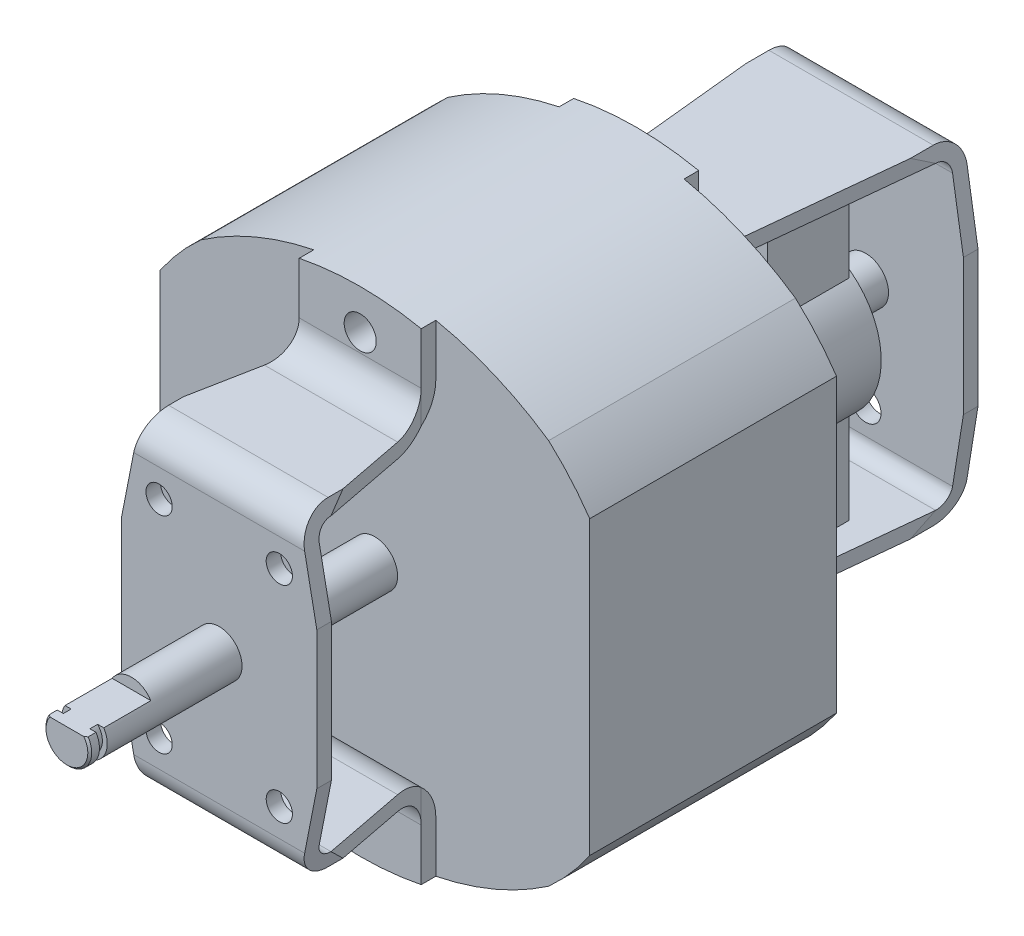
SolidWorks part; units mm, degrees
material "PW50:12:C1:0:1:2:Re:26:"
ref_plane "Plane1" through (0, 0, 0) normal (0, 0, 1) x (1, 0, 0)
ref_plane "Plane2" through (0, 0, 0) normal (0, 1, 0) x (1, 0, 0)
ref_plane "Plane3" through (0, 0, 0) normal (1, 0, 0) x (0, 0, -1)
sketch "motor core shape" plane through (0, 0, 0) normal (0, 0, 1) x (1, 0, 0)
  line L0 (-5.8998, 26.05) -> (5.8998, 26.05)
  line L1 (-22.1, 15) -> (-22.1, -15)
  line L2 (5.8998, -26.05) -> (-5.8998, -26.05)
  line L3 (22.1, -15) -> (22.1, 15)
  arc A0 (-5.8998, 26.05) -> (-22.1, 15) centre (0, 0) ccw
  arc A1 (-22.1, -15) -> (-5.8998, -26.05) centre (0, 0) ccw
  arc A2 (5.8998, -26.05) -> (22.1, -15) centre (0, 0) ccw
  arc A3 (22.1, 15) -> (5.8998, 26.05) centre (0, 0) ccw
  dimension "D1" = 44.2
  dimension "D2" = 52.1
  dimension "D3" = 30
  dimension "D4" = 11.7996
extrude "motor core" add sketch "motor core shape" along normal blind 25.38
sketch "Sketch5" plane through (0, 0, 25.38) normal (0, 0, 1) x (1, 0, 0)
  line L0 (0, 30.7658) -> (0, -31.4186) construction
  line L1 (-27.6647, 0) -> (27.0118, 0) construction
  line L2 (-5.8998, 26.05) -> (5.8998, 26.05) construction
  line L5 (8.2, 16.45) -> (10.04, 7.075)
  line L6 (-8.2, 16.45) -> (-10.04, 7.075)
  line L7 (10.04, 7.075) -> (10.04, -7.075)
  line L8 (-10.04, 7.075) -> (-10.04, -7.075)
  line L9 (-8.2, -16.45) -> (-10.04, -7.075)
  line L10 (8.2, -16.45) -> (10.04, -7.075)
  line L15 (-8.2, 16.45) -> (8.2, 16.45)
  line L16 (-8.2, -16.45) -> (8.2, -16.45)
  point P9 (0, 25.95)
  point P16 (-10.04, 0)
  point P17 (10.04, 0)
  point P21 (0, -25.95)
  dimension "D1" = 16.4
  dimension "D2" = 9.6
  dimension "D4" = 20.08
  dimension "D5" = 14.15
extrude "gear end plate" add sketch "Sketch5" along normal blind 16
fillet "gear end plate fillet" radius 3 2 edges at (0, -16.45, 41.38) (-8.2, 16.45, 33.38)
sketch "Sketch7" plane through (-10.04, 0, 0) normal (-1, 0, 0) x (0, 0, 1)
  line L0 (25.38, 15) -> (25.38, -15) construction
  line L1 (25.38, 14.95) -> (25.38, -14.95)
  line L5 (38.38, -14.95) -> (25.38, -14.95)
  line L6 (39.88, -13.45) -> (39.88, -7.075)
  line L7 (39.88, 7.075) -> (39.88, -7.075)
  line L8 (39.88, 13.45) -> (39.88, 7.075)
  line L9 (38.38, 14.95) -> (25.38, 14.95)
  line L10 (38.38, -14.95) -> (25.38, -14.95)
  line L11 (39.88, -13.45) -> (39.88, -7.075)
  line L12 (39.88, 7.075) -> (39.88, -7.075)
  line L13 (39.88, 13.45) -> (39.88, 7.075)
  line L14 (38.38, 14.95) -> (25.38, 14.95)
  arc A2 (38.38, -14.95) -> (39.88, -13.45) centre (38.38, -13.45) ccw
  arc A3 (39.88, 13.45) -> (38.38, 14.95) centre (38.38, 13.45) ccw
  arc A4 (38.38, -14.95) -> (39.88, -13.45) centre (38.38, -13.45) ccw
  arc A5 (39.88, 13.45) -> (38.38, 14.95) centre (38.38, 13.45) ccw
  dimension "D1" = 1.5
extrude "gear end plate cut" cut sketch "Sketch7" against normal through all
sketch "Sketch8" plane through (0, 0, 25.38) normal (0, 0, 1) x (1, 0, 0)
  line L0 (0, 16.45) -> (0, -16.45) construction
  line L1 (6.275, 25.95) -> (6.275, 16.45)
  line L2 (-30.1129, 0) -> (30.1129, 0) construction
  line L3 (-6.275, -25.95) -> (-6.275, -16.45)
  line L4 (5.8998, -25.95) -> (-5.8998, -25.95)
  line L5 (6.275, -25.95) -> (-6.275, -25.95)
  line L6 (-6.275, 25.95) -> (-6.275, 16.45)
  line L7 (6.275, -25.95) -> (6.275, -16.45)
  line L8 (8.2, -16.45) -> (-8.2, -16.45) construction
  line L9 (6.275, 16.45) -> (-6.275, 16.45)
  line L10 (6.275, -16.45) -> (-6.275, -16.45)
  line L12 (6.275, 25.95) -> (-6.275, 25.95)
  point P19 (0, 0)
  dimension "D2" = 12.55
  dimension "D1" = 0.1
extrude "gear end plate tabs" add sketch "Sketch8" along normal blind 1.5
sketch "Sketch9" plane through (0, -16.45, 0) normal (0, -1, 0) x (1, 0, 0)
  line L0 (-8.2, 25.38) -> (-6.275, 25.38) construction
  line L1 (6.275, 25.38) -> (8.2, 25.38) construction
  line L2 (-8.4944, 25.38) -> (-6.275, 25.38)
  line L3 (6.275, 25.38) -> (8.4944, 25.38)
  line L6 (-8.4944, 38.38) -> (-8.4944, 25.38) construction
  line L7 (8.4944, 38.38) -> (6.275, 26.88)
  line L8 (-6.275, 26.88) -> (-6.275, 25.38) construction
  line L9 (6.275, 26.88) -> (6.275, 25.38) construction
  line L10 (-6.275, 26.88) -> (-6.275, 25.38)
  line L11 (6.275, 26.88) -> (6.275, 25.38)
  line L12 (-6.275, 26.88) -> (-8.4944, 38.38)
  line L13 (-8.4944, 38.38) -> (-8.4944, 25.38)
  line L14 (8.4944, 38.38) -> (8.4944, 25.38) construction
  line L15 (8.4944, 38.38) -> (8.4944, 25.38)
extrude "gear end side cut" cut sketch "Sketch9" against normal through all
fillet "gear end tab fillet" radius 3 2 edges at (0, -16.45, 26.88) (0, 16.45, 26.88)
sketch "Sketch10" plane through (-6.275, 0, 0) normal (-1, 0, 0) x (0, 0, 1)
  line L0 (25.38, 19.45) -> (25.38, 14.95)
  line L2 (29.88, 14.95) -> (25.38, 14.95)
  line L3 (29.88, -14.95) -> (25.38, -14.95)
  line L4 (25.38, -19.45) -> (25.38, -14.95)
  arc A3 (25.38, 19.45) -> (29.88, 14.95) centre (29.88, 19.45) ccw
  arc A4 (25.38, 19.45) -> (29.88, 14.95) centre (29.88, 19.45) ccw
  arc A5 (29.88, -14.95) -> (25.38, -19.45) centre (29.88, -19.45) ccw
  arc A6 (29.88, -14.95) -> (25.38, -19.45) centre (29.88, -19.45) ccw
  dimension "D1" = 1.5
  dimension "D2" = 1.5
extrude "gear end kludge fillet" cut sketch "Sketch10" against normal through all and the other way through all
sketch "Sketch11" plane through (0, 0, 41.38) normal (0, 0, 1) x (1, 0, 0)
  line L0 (0, -20.7281) -> (0, 30.0313) construction
  line L1 (-15.0973, 0) -> (30.1129, 0) construction
  circle A0 centre (6.1825, 10.5986) radius 1.35
  circle A1 centre (-6.1825, 10.5986) radius 1.35
  circle A2 centre (-6.1825, -10.5986) radius 1.35
  circle A3 centre (6.1825, -10.5986) radius 1.35
  dimension "D1" = 27.24
  dimension "D2" = 2.7
extrude "gear caddy screw holes" cut sketch "Sketch11" against normal up to next
sketch "Sketch13" plane through (0, 0, 0) normal (0, 0, -1) x (-1, 0, 0)
  line L0 (0, 16.95) -> (0, -16.95) construction
  line L1 (-10.05, 0) -> (10.05, 0) construction
  line L2 (-8.45, 16.95) -> (8.45, 16.95)
  line L3 (8.45, 16.95) -> (10.05, 7)
  line L4 (-10.05, 7) -> (-10.05, -7)
  line L5 (10.05, 7) -> (10.05, -7)
  line L6 (-8.45, 16.95) -> (-10.05, 7)
  line L7 (-8.45, -16.95) -> (-10.05, -7)
  line L8 (8.45, -16.95) -> (10.05, -7)
  line L9 (-8.45, -16.95) -> (8.45, -16.95)
  point P5 (-10.05, 0)
  point P10 (0, 16.45)
  point P12 (0, 16.95)
  point P15 (-10.04, 0)
  point P16 (10.04, 0)
  point P17 (10.05, 0)
  point P18 (0, -16.45)
  point P19 (0, -16.95)
  dimension "D1" = 14
  dimension "D2" = 33.9
  dimension "D3" = 16.9
  dimension "D4" = 20.1
extrude "rotor end plate" add sketch "Sketch13" along normal blind 26.6
fillet "rotor end plate fillet" radius 3 2 edges at (0, 16.95, -26.6) (8.45, -16.95, -13.3)
sketch "Sketch14" plane through (10.05, 0, 0) normal (1, 0, 0) x (0, 0, -1)
  line L0 (0, -15) -> (0, 15) construction
  line L1 (0, -15.45) -> (0, 15.45)
  line L5 (23.6, -15.45) -> (0, -15.45)
  line L6 (25.1, -13.95) -> (25.1, -7)
  line L7 (25.1, 7) -> (25.1, -7)
  line L8 (25.1, 13.95) -> (25.1, 7)
  line L9 (23.6, 15.45) -> (0, 15.45)
  line L10 (23.6, -15.45) -> (0, -15.45)
  line L11 (25.1, -13.95) -> (25.1, -7)
  line L12 (25.1, 7) -> (25.1, -7)
  line L13 (25.1, 13.95) -> (25.1, 7)
  line L14 (23.6, 15.45) -> (0, 15.45)
  arc A2 (23.6, -15.45) -> (25.1, -13.95) centre (23.6, -13.95) ccw
  arc A3 (25.1, 13.95) -> (23.6, 15.45) centre (23.6, 13.95) ccw
  arc A4 (23.6, -15.45) -> (25.1, -13.95) centre (23.6, -13.95) ccw
  arc A5 (25.1, 13.95) -> (23.6, 15.45) centre (23.6, 13.95) ccw
  dimension "D1" = 1.5
extrude "rotor end plate cut" cut sketch "Sketch14" against normal through all and the other way through all
sketch "Sketch15" plane through (0, 0, 0) normal (0, 0, -1) x (-1, 0, 0)
  line L0 (-6.425, 25.95) -> (6.425, 25.95)
  line L1 (-6.425, 25.95) -> (-6.425, 16.95)
  line L2 (-8.45, 16.95) -> (8.45, 16.95) construction
  line L3 (-6.425, 16.95) -> (6.425, 16.95)
  line L4 (0, 30.1945) -> (0, -31.9899) construction
  line L5 (-30.3577, 0) -> (31.9899, 0) construction
  line L6 (6.425, 25.95) -> (6.425, 16.95)
  line L7 (6.425, -25.95) -> (6.425, -16.95)
  line L8 (-6.425, -16.95) -> (6.425, -16.95)
  line L9 (-6.425, -25.95) -> (-6.425, -16.95)
  line L10 (-6.425, -25.95) -> (6.425, -25.95)
  line L11 (5.8998, 26.05) -> (-5.8998, 26.05) construction
  point P13 (0, 16.95)
  point P14 (0, 25.95)
  point P18 (0, -25.95)
  point P19 (0, -16.95)
  dimension "D1" = 12.85
  dimension "D2" = 0.1
extrude "rotor end plate tabs" add sketch "Sketch15" along normal blind 1.5
sketch "Sketch16" plane through (0, -16.95, 0) normal (0, -1, 0) x (1, 0, 0)
  line L2 (-8.6912, -23.6) -> (-8.6912, 0) construction
  line L3 (-6.425, -1.5) -> (-6.425, 0) construction
  line L4 (6.425, -1.5) -> (6.425, 0) construction
  line L5 (8.6912, -23.6) -> (8.6912, 0) construction
  line L6 (-8.6912, -23.6) -> (-8.6912, 0)
  line L7 (-6.425, -1.5) -> (-6.425, 0)
  line L8 (6.425, -1.5) -> (6.425, 0)
  line L9 (8.6912, -23.6) -> (8.6912, 0)
  line L10 (8.6912, 0) -> (6.425, 0)
  line L11 (6.425, -1.5) -> (8.6912, -23.6)
  line L12 (-6.425, 0) -> (-8.6912, 0)
  line L13 (-6.425, -1.5) -> (-8.6912, -23.6)
extrude "rotor end side ct" cut sketch "Sketch16" against normal through all and the other way through all
fillet "rotor end tab fillet" radius 3 2 edges at (0, -16.95, -1.5) (0, 16.95, -1.5)
sketch "Sketch17" plane through (-6.425, 0, 0) normal (-1, 0, 0) x (0, 0, 1)
  line L0 (0, 19.95) -> (0, 15.45)
  line L2 (-4.5, 15.45) -> (0, 15.45)
  line L3 (0, -19.95) -> (0, -15.45)
  line L5 (-4.5, -15.45) -> (0, -15.45)
  arc A1 (-4.5, 15.45) -> (0, 19.95) centre (-4.5, 19.95) ccw
  arc A2 (-4.5, 15.45) -> (0, 19.95) centre (-4.5, 19.95) ccw
  arc A3 (0, -19.95) -> (-4.5, -15.45) centre (-4.5, -19.95) ccw
  arc A4 (0, -19.95) -> (-4.5, -15.45) centre (-4.5, -19.95) ccw
  dimension "D1" = 1.5
  dimension "D2" = 1.5
extrude "rotor end kludge fillet" cut sketch "Sketch17" against normal through all and the other way through all
sketch "Sketch12" plane through (0, 0, 0) normal (0, 0, -1) x (-1, 0, 0)
  line L0 (-28.8072, 0) -> (27.0118, 0) construction
  line L1 (5.8998, 26.05) -> (-5.8998, 26.05) construction
  circle A0 centre (0, 21.3) radius 1.65
  circle A1 centre (0, -21.3) radius 1.65
  dimension "D1" = 3.3
  dimension "D2" = 4.75
extrude "motor long screw holes" cut sketch "Sketch12" against normal through all and the other way through all
sketch "Sketch1" plane through (0, 0, 25.38) normal (0, 0, 1) x (1, 0, 0)
  circle A0 centre (0, 0) radius 2.35
  dimension "D1" = 4.7
extrude "motor shaft" add sketch "Sketch1" along normal blind 31.66 and the other way offset from surface (54.08 mm away) 28.7 other way up to face at (0, -26.0004, 0)
sketch "Sketch3" plane through (0, 0, 57.04) normal (0, 0, 1) x (1, 0, 0)
  circle A0 centre (0, 0) radius 2.35 construction
  circle A1 centre (0, 0) radius 1.85
  circle A2 centre (0, 0) radius 1.85
  circle A3 centre (0, 0) radius 2.35
  dimension "D1" = 0.5
extrude "groove cut" cut sketch "Sketch3" against normal blind 1.8
sketch "Sketch4" plane through (0, 0, 57.04) normal (0, 0, 1) x (1, 0, 0)
  circle A0 centre (0, 0) radius 2.35 construction
  circle A1 centre (0, 0) radius 2.35
extrude "groove fill" add sketch "Sketch4" against normal offset from surface (1 mm away) 0.8 up to face at (1.85, 0, 55.24)
chamfer "shaft chamfer" distance 0.2 angle 45 1 edges at (2.35, 0, 57.04)
sketch "Sketch2" plane through (0, 0, 57.04) normal (0, 0, 1) x (1, 0, 0)
  line L0 (-1.99, 1.25) -> (1.99, 1.25)
  circle A0 centre (0, 0) radius 2.35 construction
  arc A1 (1.99, 1.25) -> (-1.99, 1.25) centre (0, 0) ccw
  dimension "D1" = 3.6
extrude "motor gear flat" cut sketch "Sketch2" against normal blind 6.64
sketch "Sketch18" plane through (0, 0, -26.6) normal (0, 0, -1) x (-1, 0, 0)
  line L0 (-33.3772, 0) -> (32.8875, 0) construction
  circle A0 centre (0, 11.12) radius 1.58
  circle A1 centre (0, -11.12) radius 1.58
  dimension "D1" = 3.16
  dimension "D2" = 25.4
extrude "rotor end plate holes" cut sketch "Sketch18" against normal up to next
ref_plane "Plane4" through (0, 0, -18.7) normal (0, 0, -1) x (-1, 0, 0)
sketch "Sketch20" plane through (0, 0, -18.7) normal (0, 0, -1) x (-1, 0, 0)
  circle A1 centre (0, 0) radius 2.35 construction
  circle A2 centre (0, 0) radius 2.35
  circle A3 centre (0, 0) radius 8
  dimension "D1" = 16
extrude "motor rotor" add sketch "Sketch20" against normal blind 12
sketch "Sketch21" plane through (0, 16.95, 0) normal (0, 1, 0) x (-1, 0, 0)
  line L0 (0, 0) -> (0, -32.7148) construction
  line L1 (0, 0) -> (0, -6.7) construction
  line L2 (5.1372, -18.2466) -> (-5.1372, -18.2466)
  line L3 (-5.1372, -18.2466) -> (-5.1372, -9.8593)
  line L4 (5.1372, -18.2466) -> (5.1372, -9.8593)
  line L5 (-5.1372, -9.8593) -> (5.1372, -9.8593)
  point P8 (0, -18.2466)
  point P11 (0, -9.8593)
extrude "motor stator,brushes" add sketch "Sketch21" along normal up to surface (33.9 mm away)
sketch "Sketch22" plane through (0, 0, 26.88) normal (0, 0, 1) x (1, 0, 0)
  line L0 (0, 0) -> (15.3278, 0) construction
  line L1 (28.8072, 0) -> (-27.0118, 0) construction
  line L3 (-5.8998, 26.05) -> (6.425, 25.9255)
  line L4 (-5.8998, -26.05) -> (6.425, -25.9255)
  arc A0 (31.4115, -2.6863) -> (-31.3668, -2.3101) centre (0, -6.2245) ccw construction
  arc A1 (17.8771, -19.8448) -> (6.425, -25.9255) centre (0, 0) cw
  arc A2 (-5.8998, -26.05) -> (-17.8771, -19.8448) centre (0, 0) cw
  arc A3 (17.8771, 19.8448) -> (-17.8771, 19.8448) centre (0, -6.2245) ccw
  arc A4 (-5.8998, 26.05) -> (-6.3251, 25.95) centre (0, 0) ccw construction
  arc A5 (-5.8998, 26.05) -> (-17.8771, 19.8448) centre (0, 0) ccw
  arc A6 (22.1, 15) -> (6.425, 25.9255) centre (0, 0) ccw construction
  arc A7 (17.8771, 19.8448) -> (6.425, 25.9255) centre (0, 0) ccw
  arc A8 (17.8771, -19.8448) -> (-17.8771, -19.8448) centre (0, 6.2245) cw
extrude "Cut-Extrude1" cut sketch "Sketch22" against normal through all
